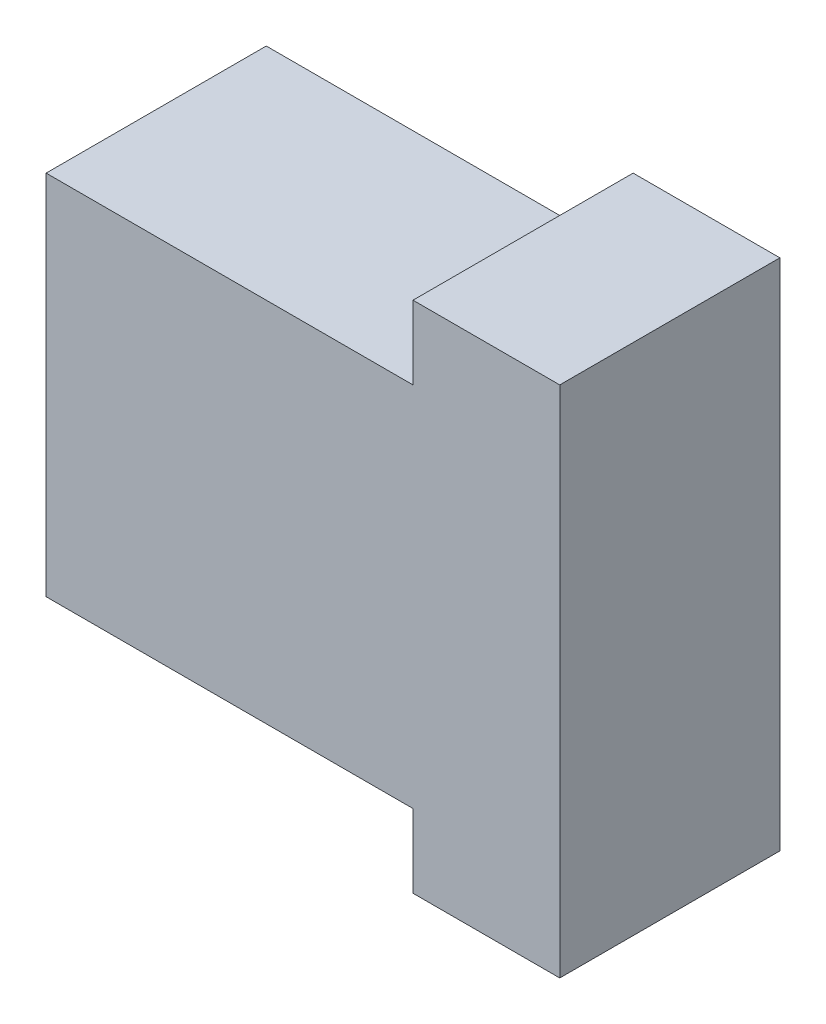
SolidWorks part; units mm, degrees
ref_plane "Alzado" through (0, 0, 0) normal (0, 0, 1) x (1, 0, 0)
ref_plane "Planta" through (0, 0, 0) normal (0, 1, 0) x (1, 0, 0)
ref_plane "Vista lateral" through (0, 0, 0) normal (1, 0, 0) x (0, 0, -1)
sketch "Croquis1" plane through (0, 0, 0) normal (0, 0, 1) x (1, 0, 0)
  line L1 (-12.9538, 8.0023) -> (-7.9538, 8.0023)
  line L2 (-12.9538, 8.0023) -> (-12.9538, 3.0023)
  line L3 (-12.9538, 3.0023) -> (-7.9538, 3.0023)
  line L4 (-7.9538, 8.0023) -> (-7.9538, 3.0023)
  line L5 (-7.9538, 9.0023) -> (-5.9538, 9.0023)
  line L6 (-7.9538, 9.0023) -> (-7.9538, 2.0023)
  line L7 (-7.9538, 2.0023) -> (-5.9538, 2.0023)
  line L8 (-5.9538, 9.0023) -> (-5.9538, 2.0023)
  point P8 (0, 0)
  dimension "D1" = 5
  dimension "D2" = 5
  dimension "D3" = 7
  dimension "D4" = 1
  dimension "D5" = 2
extrude "Saliente-Extruir1" add sketch "Croquis1" along normal blind 3 contours L4 L1 L2 L3 | L8 L5 L6 L4 L7
